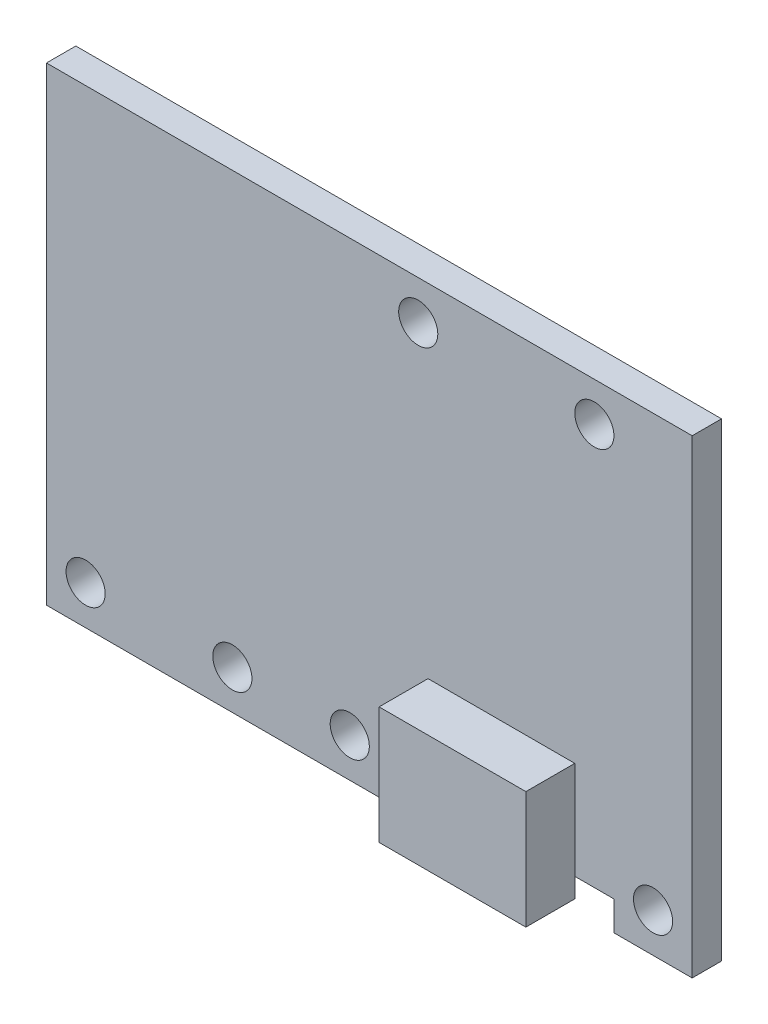
SolidWorks part; units mm, degrees
ref_plane "Front" through (0, 0, 0) normal (0, 0, 1) x (1, 0, 0)
ref_plane "Top" through (0, 0, 0) normal (0, 1, 0) x (1, 0, 0)
ref_plane "Right" through (0, 0, 0) normal (1, 0, 0) x (0, 0, -1)
sketch "Эскиз1" plane through (0, 0, 0) normal (0, 0, 1) x (1, 0, 0)
  line L1 (-16.5, 12) -> (16.5, 12)
  line L2 (-16.5, 12) -> (-16.5, -12)
  line L3 (-16.5, -12) -> (16.5, -12)
  line L4 (16.5, 12) -> (16.5, -12)
  line L5 (-16.5, 12) -> (16.5, -12) construction
  line L6 (-16.5, -12) -> (16.5, 12) construction
  line L7 (12.5, -12) -> (1, -12)
  line L8 (12.5, -12) -> (12.5, -10.5)
  line L9 (12.5, -10.5) -> (1, -10.5)
  line L10 (1, -12) -> (1, -10.5)
  circle A0 centre (14.5, -10) radius 1
  circle A1 centre (-1, -10) radius 1
  circle A2 centre (-7, -10) radius 1
  circle A3 centre (-14.5, -10) radius 1
  circle A4 centre (2.5, 10) radius 1
  circle A5 centre (11.5, 10) radius 1
  point P0 (0, 0)
  point P24 (8.0724, 7.5604)
  dimension "D6" = 2
  dimension "D9" = 2
  dimension "D1" = 24
  dimension "D2" = 33
  dimension "D3" = 4
  dimension "D4" = 11.5
  dimension "D5" = 1.5
  dimension "D7" = 2
  dimension "D8" = 2
  dimension "D10" = 2
  dimension "D11" = 7.5
  dimension "D12" = 5
  dimension "D13" = 9
  dimension "D14" = 2
extrude "Бобышка-Вытянуть1" add sketch "Эскиз1" against normal blind 1.5 contours L3 L10 L9 L8 L4 L1 L2 A5 A4 A3 A2 A1 A0
sketch "Эскиз2" plane through (0, 0, 0) normal (0, 0, 1) x (1, 0, 0)
  line L0 (12.5, -10.5) -> (1, -10.5) construction
  line L1 (3, -5.5) -> (10.5, -5.5)
  line L2 (3, -5.5) -> (3, -11.5)
  line L3 (3, -11.5) -> (10.5, -11.5)
  line L4 (10.5, -5.5) -> (10.5, -11.5)
  line L5 (3, -5.5) -> (10.5, -11.5) construction
  line L6 (3, -11.5) -> (10.5, -5.5) construction
  line L7 (-16.5, 12) -> (16.5, 12) construction
  point P0 (6.75, -8.5)
  point P5 (6.75, -10.5)
  dimension "D1" = 6
  dimension "D2" = 7.5
  dimension "D3" = 17.5
extrude "Бобышка-Вытянуть2" add sketch "Эскиз2" along normal blind 2.5
